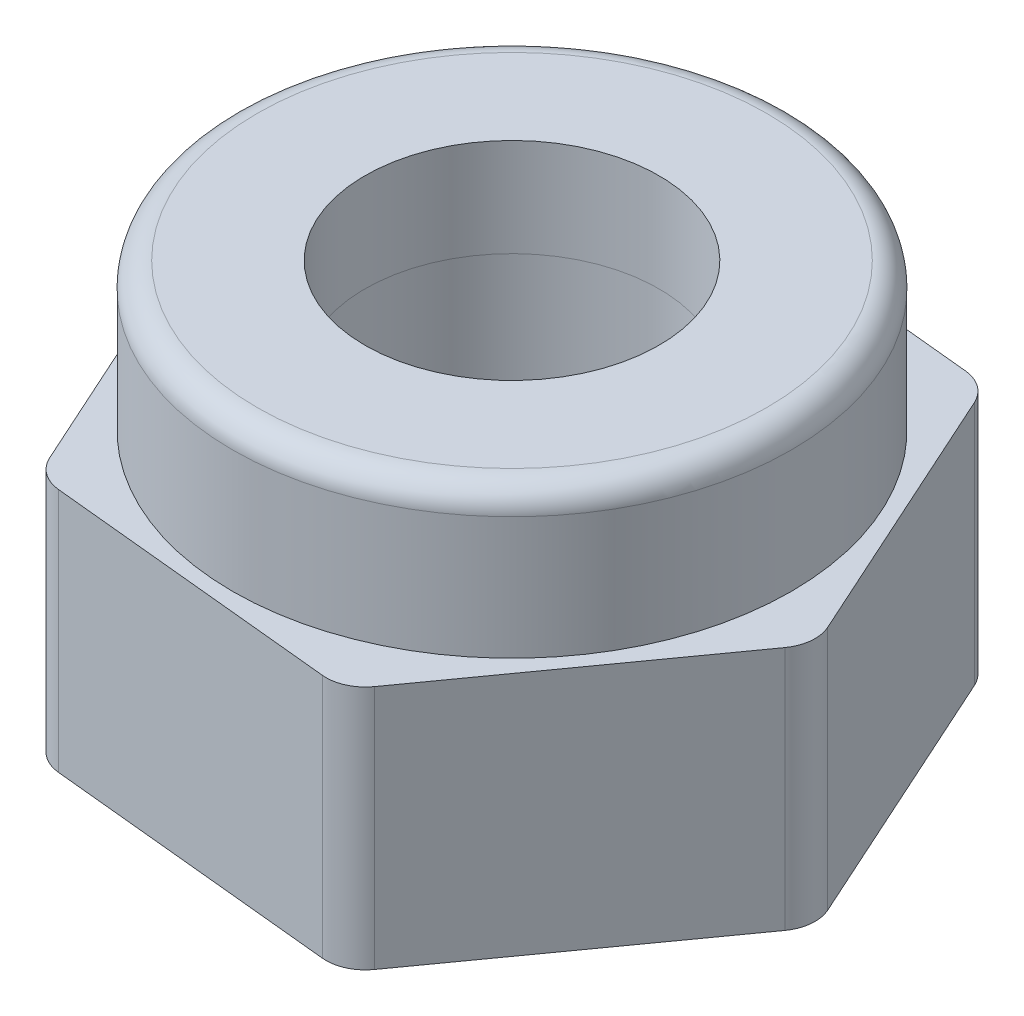
SolidWorks part; units mm, degrees
ref_plane "Front Plane" through (0, 0, 0) normal (0, 0, 1) x (1, 0, 0)
ref_plane "Top Plane" through (0, 0, 0) normal (0, 1, 0) x (1, 0, 0)
ref_plane "Right Plane" through (0, 0, 0) normal (1, 0, 0) x (0, 0, -1)
sketch "Sketch1" plane through (0, 0, 0) normal (0, 1, 0) x (1, 0, 0)
  line L1 (1.4285, -3.1559) -> (3.4473, -0.3408)
  line L2 (3.4473, -0.3408) -> (2.0188, 2.815)
  line L3 (2.0188, 2.815) -> (-1.4285, 3.1559)
  line L4 (-1.4285, 3.1559) -> (-3.4473, 0.3408)
  line L5 (-3.4473, 0.3408) -> (-2.0188, -2.815)
  line L6 (-2.0188, -2.815) -> (1.4285, -3.1559)
  circle A0 centre (0, 0) radius 3 construction
extrude "Boss-Extrude1" add sketch "Sketch1" along normal blind 2.5
fillet "Fillet1" radius 0.4 6 edges at (-3.4473, 1.25, -0.3408) (-1.4285, 1.25, -3.1559) (2.0188, 1.25, -2.815) (3.4473, 1.25, 0.3408) (1.4285, 1.25, 3.1559) (-2.0188, 1.25, 2.815)
sketch "Sketch2" plane through (0, 2.5, 0) normal (0, 1, 0) x (1, 0, 0)
  circle A0 centre (0, 0) radius 2.85
extrude "Boss-Extrude2" add sketch "Sketch2" along normal blind 1.5
fillet "Fillet2" radius 0.25 1 edges at (0, 4, 2.85)
sketch "Sketch5" plane through (0, 4, 0) normal (0, 1, 0) x (1, 0, 0)
  circle A0 centre (0, 0) radius 2.6
  circle A1 centre (0, 0) radius 1.25
extrude "Cut-Extrude2" cut sketch "Sketch5" against normal blind 1
sketch "Sketch6" plane through (0, 3, 0) normal (0, 1, 0) x (1, 0, 0)
  circle A0 centre (0, 0) radius 2.6
extrude "Boss-Extrude6" add sketch "Sketch6" along normal blind 1 separate body
sketch "Sketch7" plane through (0, 4, 0) normal (0, 1, 0) x (1, 0, 0)
  circle A0 centre (0, 0) radius 1.5
extrude "Cut-Extrude3" cut sketch "Sketch7" against normal through all
